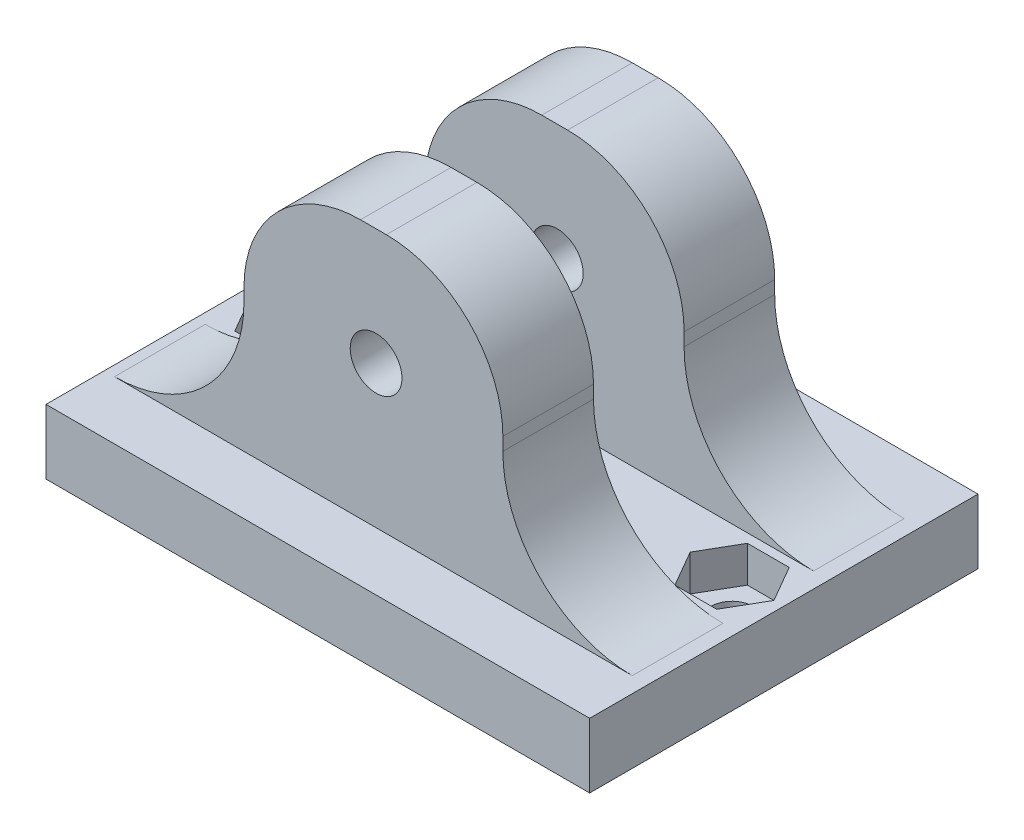
SolidWorks part; units mm, degrees
ref_plane "Alzado" through (0, 0, 0) normal (0, 0, 1) x (1, 0, 0)
ref_plane "Planta" through (0, 0, 0) normal (0, 1, 0) x (1, 0, 0)
ref_plane "Vista lateral" through (0, 0, 0) normal (1, 0, 0) x (0, 0, -1)
sketch "Croquis1" plane through (0, 0, 0) normal (0, 0, 1) x (1, 0, 0)
  line L1 (-21, 0) -> (21, 0)
  line L2 (-21, 0) -> (-21, 5)
  line L3 (-21, 5) -> (21, 5)
  line L4 (21, 0) -> (21, 5)
  point P4 (0, 0)
  dimension "D1" = 5
  dimension "D2" = 42
extrude "Saliente-Extruir1" add sketch "Croquis1" along normal blind 30
sketch "Croquis2" plane through (0, 5, 0) normal (0, 1, 0) x (1, 0, 0)
  line L0 (-21, -15) -> (-13, -15) construction
  line L1 (-21, -30) -> (-21, 0) construction
  line L2 (0, 0) -> (0, -30) construction
  line L3 (21, -30) -> (-21, -30) construction
  circle A0 centre (-17, -15) radius 1.6
  circle A1 centre (17, -15) radius 1.6
  dimension "D2" = 3.2
  dimension "D1" = 8
extrude "Cortar-Extruir1" cut sketch "Croquis2" against normal blind 21 and the other way blind 15
sketch "Croquis3" plane through (0, 5, 0) normal (0, 1, 0) x (1, 0, 0)
  line L0 (0, 0) -> (0, -30) construction
  line L1 (21, 0) -> (-21, 0) construction
  line L2 (21, -30) -> (-21, -30) construction
  line L3 (15.3834, -17.8) -> (13.7668, -15)
  line L4 (-13.7668, -15) -> (-15.3834, -12.2)
  line L5 (-15.3834, -12.2) -> (-18.6166, -12.2)
  line L6 (-18.6166, -12.2) -> (-20.2332, -15)
  line L7 (-20.2332, -15) -> (-18.6166, -17.8)
  line L8 (-18.6166, -17.8) -> (-15.3834, -17.8)
  line L9 (-15.3834, -17.8) -> (-13.7668, -15)
  line L10 (18.6166, -17.8) -> (15.3834, -17.8)
  line L11 (20.2332, -15) -> (18.6166, -17.8)
  line L12 (18.6166, -12.2) -> (20.2332, -15)
  line L13 (15.3834, -12.2) -> (18.6166, -12.2)
  line L14 (13.7668, -15) -> (15.3834, -12.2)
  circle A0 centre (-17, -15) radius 2.8 construction
  dimension "D1" = 5.6
extrude "Cortar-Extruir2" cut sketch "Croquis3" against normal blind 2.8
sketch "Croquis4" plane through (0, 5, 0) normal (0, 1, 0) x (1, 0, 0)
  line L0 (0, 0) -> (0, -30) construction
  line L5 (-10.2054, -25.5) -> (9.7946, -25.5)
  line L6 (9.7946, -25.5) -> (9.7946, -18.5)
  line L7 (21, 0) -> (-21, 0) construction
  line L8 (21, -30) -> (-21, -30) construction
  line L14 (-10.2054, -18.5) -> (9.7946, -18.5)
  line L15 (-10.2054, -25.5) -> (-10.2054, -18.5)
  line L17 (-21, -15) -> (21, -15) construction
  line L18 (-21, -30) -> (-21, 0) construction
  line L19 (21, -30) -> (21, 0) construction
  line L20 (-10.2054, -4.5) -> (-10.2054, -11.5)
  line L21 (-10.2054, -4.5) -> (9.7946, -4.5)
  line L22 (9.7946, -4.5) -> (9.7946, -11.5)
  line L23 (-10.2054, -11.5) -> (9.7946, -11.5)
  point P0 (0, -15)
  point P12 (0, -15)
  dimension "D1" = 21
extrude "Saliente-Extruir2" add sketch "Croquis4" along normal blind 20
fillet "Fillet1" radius 9 4 edges at (9.7946, 25, 8) (9.7946, 25, 22) (-10.2054, 25, 22) (-10.2054, 25, 8)
sketch "Sketch1" plane through (0, 0, 25.5) normal (0, 0, 1) x (1, 0, 0)
  circle A0 centre (0, 16) radius 2
  dimension "D1" = 4
extrude "Cut-Extrude1" cut sketch "Sketch1" against normal blind 32 and the other way blind 15
fillet "Fillet2" radius 10 4 edges at (9.7946, 5, 8) (9.7946, 5, 22) (-10.2054, 5, 22) (-10.2054, 5, 8)
